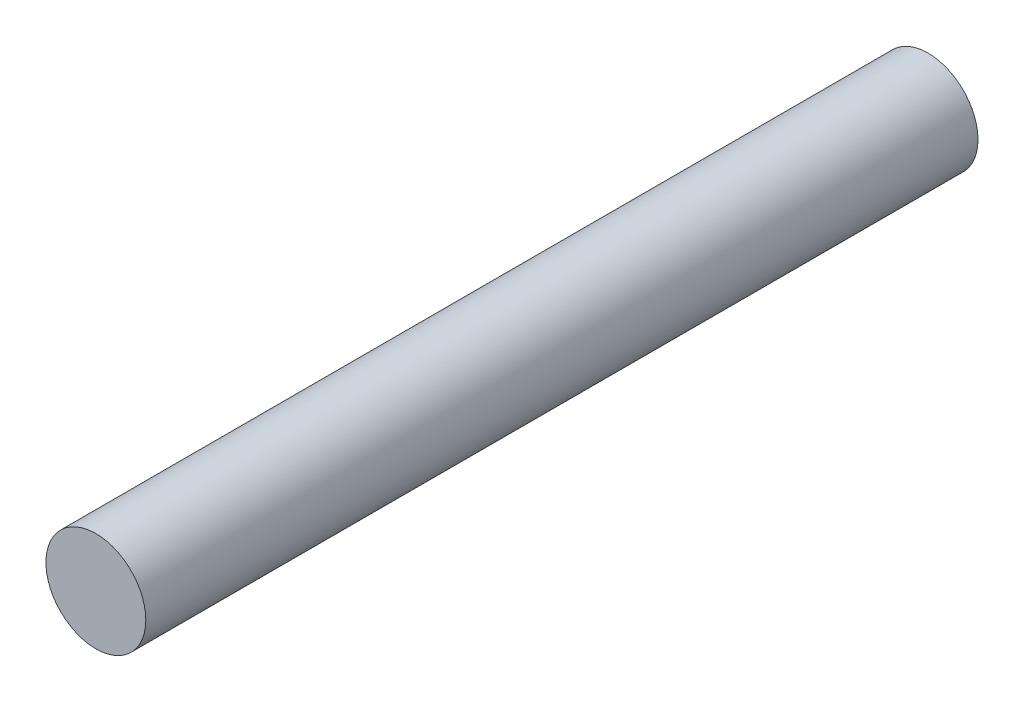
SolidWorks part; units mm, degrees
ref_plane "前基準面" through (0, 0, 0) normal (0, 0, 1) x (1, 0, 0)
ref_plane "上基準面" through (0, 0, 0) normal (0, 1, 0) x (1, 0, 0)
ref_plane "右基準面" through (0, 0, 0) normal (1, 0, 0) x (0, 0, -1)
sketch "草圖1" plane through (0, 0, 0) normal (0, 0, 1) x (1, 0, 0)
  circle A0 centre (0, 0) radius 1.5
  dimension "D1" = 3
extrude "伸長1" add sketch "草圖1" along normal blind 25
